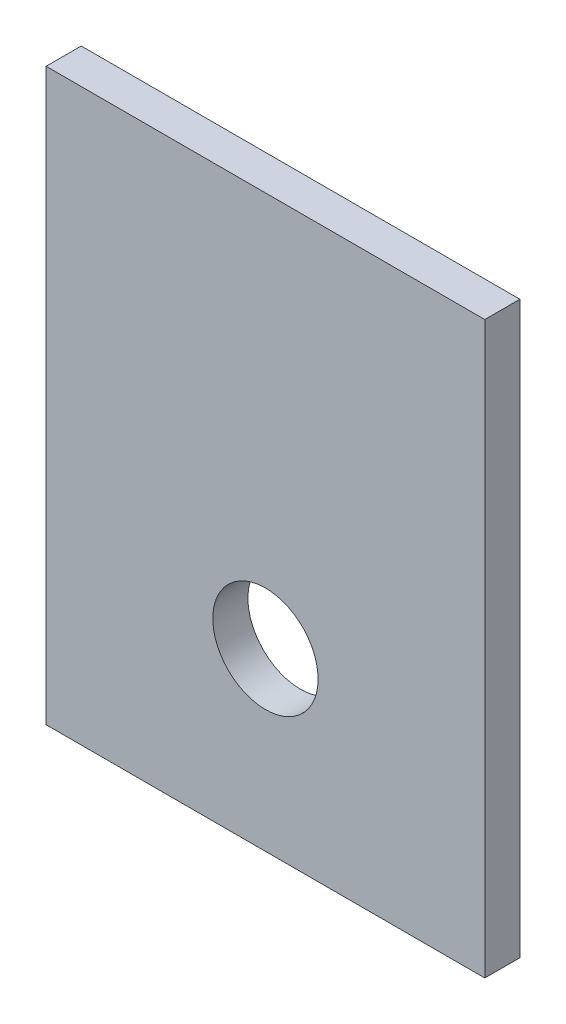
SolidWorks part; units mm, degrees
material "1060 Alloy"
ref_plane "Front Plane" through (0, 0, 0) normal (0, 0, 1) x (1, 0, 0)
ref_plane "Top Plane" through (0, 0, 0) normal (0, 1, 0) x (1, 0, 0)
ref_plane "Right Plane" through (0, 0, 0) normal (1, 0, 0) x (0, 0, -1)
sketch "Sketch2" plane through (0, 0, 0) normal (0, 0, 1) x (1, 0, 0)
  line L1 (-25, -45) -> (25, -45)
  line L2 (-25, -45) -> (-25, 45)
  line L3 (-25, 45) -> (25, 45)
  line L4 (25, -45) -> (25, 45)
  line L5 (-25, -45) -> (25, 45) construction
  line L6 (-25, 45) -> (25, -45) construction
  point P0 (0, 0)
  dimension "D1" = 50
  dimension "D2" = 90
extrude "Boss-Extrude1" add sketch "Sketch2" along normal blind 4
sketch "Sketch3" plane through (0, 0, 4) normal (0, 0, 1) x (1, 0, 0)
  line L0 (-25, -45) -> (25, -45) construction
  circle A0 centre (0, -25) radius 6
  dimension "D1" = 12
  dimension "D2" = 20
extrude "Cut-Extrude1" cut sketch "Sketch3" against normal blind 4
sketch "Sketch4" plane through (0, 0, 4) normal (0, 0, 1) x (1, 0, 0)
  line L0 (-25, 20) -> (25, 20)
  line L1 (-25, 45) -> (-25, -45) construction
  line L2 (25, -45) -> (25, 45) construction
  line L3 (25, 20) -> (25, 45)
  line L4 (25, 45) -> (-25, 45)
  line L5 (-25, 45) -> (-25, 20)
  dimension "D1" = 25
extrude "Cut-Extrude2" cut sketch "Sketch4" against normal blind 10
